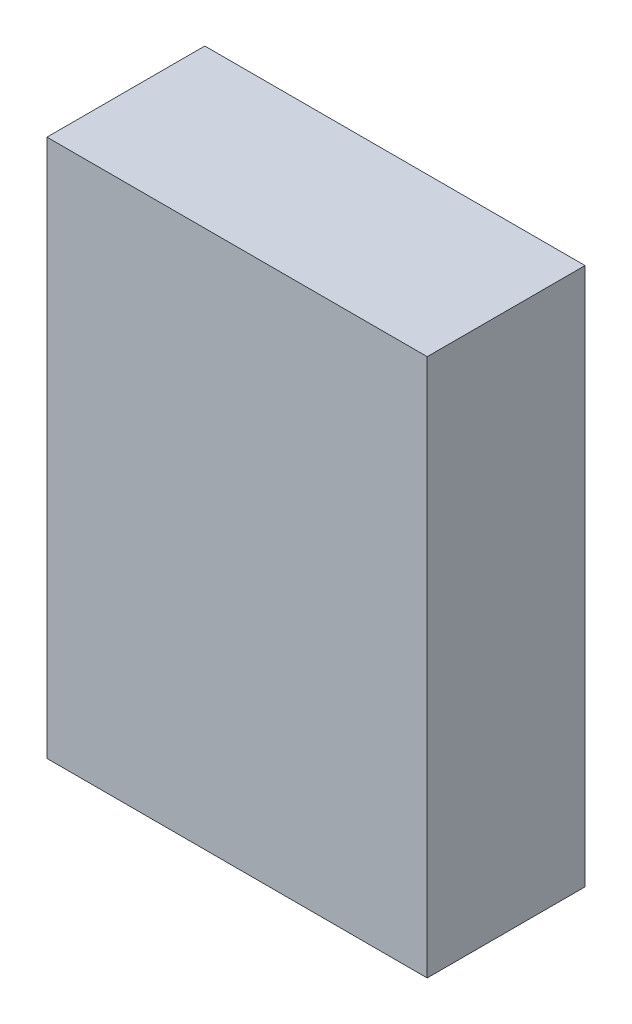
SolidWorks part; units mm, degrees
ref_plane "Front Plane" through (0, 0, 0) normal (0, 0, 1) x (1, 0, 0)
ref_plane "Top Plane" through (0, 0, 0) normal (0, 1, 0) x (1, 0, 0)
ref_plane "Right Plane" through (0, 0, 0) normal (1, 0, 0) x (0, 0, -1)
sketch "Sketch1" plane through (0, 0, 0) normal (0, 0, 1) x (1, 0, 0)
  line L1 (-26.5, -37.5) -> (26.5, -37.5)
  line L2 (-26.5, -37.5) -> (-26.5, 37.5)
  line L3 (-26.5, 37.5) -> (26.5, 37.5)
  line L4 (26.5, -37.5) -> (26.5, 37.5)
  line L5 (-26.5, -37.5) -> (26.5, 37.5) construction
  line L6 (-26.5, 37.5) -> (26.5, -37.5) construction
  point P0 (0, 0)
extrude "Envelope" add sketch "Sketch1" along normal blind 22
